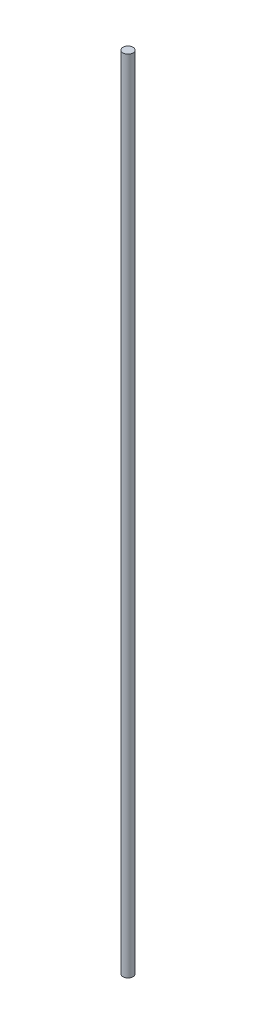
SolidWorks part; units mm, degrees
ref_plane "Plan de face" through (0, 0, 0) normal (0, 0, 1) x (1, 0, 0)
ref_plane "Plan de dessus" through (0, 0, 0) normal (0, 1, 0) x (1, 0, 0)
ref_plane "Plan de droite" through (0, 0, 0) normal (1, 0, 0) x (0, 0, -1)
sketch "Esquisse1" plane through (0, 0, 0) normal (0, 1, 0) x (1, 0, 0)
  circle A0 centre (0, 0) radius 2.5
  dimension "D1" = 5
extrude "Boss.-Extru.1" add sketch "Esquisse1" along normal blind 400
